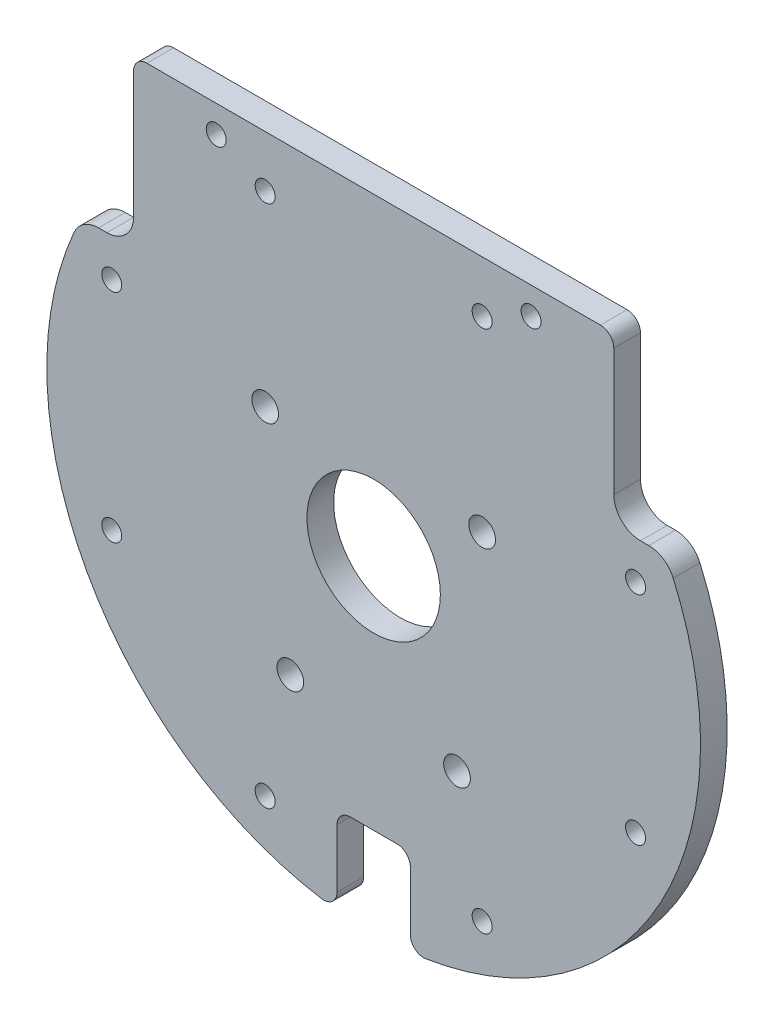
SolidWorks part; units mm, degrees
material "Hexcel AS4C (3000 丝)"
ref_plane "前视基准面" through (0, 0, 0) normal (0, 0, 1) x (1, 0, 0)
ref_plane "上视基准面" through (0, 0, 0) normal (0, 1, 0) x (1, 0, 0)
ref_plane "右视基准面" through (0, 0, 0) normal (1, 0, 0) x (0, 0, -1)
sketch "草图1" plane through (0, 0, 0) normal (0, 0, 1) x (1, 0, 0)
  line L8 (-5.5, -46.3977) -> (-5.5, -37.6103)
  line L9 (-3.5, -35.6103) -> (3.5, -35.6103)
  line L10 (5.5, -37.6103) -> (5.5, -46.3977)
  line L11 (41.2432, 22) -> (40, 22)
  line L12 (36, 26) -> (36, 45)
  line L13 (34, 47) -> (-34, 47)
  line L14 (-36, 45) -> (-36, 26)
  line L15 (-40, 22) -> (-41.2432, 22)
  line L16 (-5.5, -46.3977) -> (-5.5, -37.6103)
  line L17 (-3.5, -35.6103) -> (3.5, -35.6103)
  line L18 (5.5, -37.6103) -> (5.5, -46.3977)
  line L19 (41.2432, 22) -> (40, 22)
  line L20 (36, 26) -> (36, 45)
  line L21 (34, 47) -> (-34, 47)
  line L22 (-36, 45) -> (-36, 26)
  line L23 (-40, 22) -> (-41.2432, 22)
  circle A1 centre (0, 0) radius 10
  circle A2 centre (0, 0) radius 10
  circle A9 centre (12.5, -21.6506) radius 2
  circle A10 centre (12.5, -21.6506) radius 2
  circle A11 centre (-12.5, -21.6506) radius 2
  circle A12 centre (-12.5, -21.6506) radius 2
  circle A15 centre (-16.264, 39.2649) radius 1.5
  circle A16 centre (-16.264, 39.2649) radius 1.5
  circle A17 centre (16.264, 39.2649) radius 1.5
  circle A18 centre (16.264, 39.2649) radius 1.5
  circle A19 centre (39.2649, 16.264) radius 1.5
  circle A20 centre (39.2649, 16.264) radius 1.5
  circle A21 centre (39.2649, -16.264) radius 1.5
  circle A22 centre (39.2649, -16.264) radius 1.5
  circle A23 centre (16.264, -39.2649) radius 1.5
  circle A24 centre (16.264, -39.2649) radius 1.5
  circle A25 centre (-16.264, -39.2649) radius 1.5
  circle A26 centre (-16.264, -39.2649) radius 1.5
  circle A27 centre (-39.2649, -16.264) radius 1.5
  circle A28 centre (-39.2649, -16.264) radius 1.5
  circle A29 centre (-39.2649, 16.264) radius 1.5
  circle A30 centre (-39.2649, 16.264) radius 1.5
  arc A42 (-44.9092, 19.6) -> (-7.8191, -48.3721) centre (0, 0) ccw
  arc A43 (-7.8191, -48.3721) -> (-5.5, -46.3977) centre (-7.5, -46.3977) ccw
  arc A44 (-3.5, -35.6103) -> (-5.5, -37.6103) centre (-3.5, -37.6103) ccw
  arc A45 (5.5, -37.6103) -> (3.5, -35.6103) centre (3.5, -37.6103) ccw
  arc A46 (5.5, -46.3977) -> (7.8191, -48.3721) centre (7.5, -46.3977) ccw
  arc A47 (7.8191, -48.3721) -> (44.9092, 19.6) centre (0, 0) ccw
  arc A48 (44.9092, 19.6) -> (41.2432, 22) centre (41.2432, 18) ccw
  arc A49 (36, 26) -> (40, 22) centre (40, 26) ccw
  arc A50 (36, 45) -> (34, 47) centre (34, 45) ccw
  arc A51 (-34, 47) -> (-36, 45) centre (-34, 45) ccw
  arc A52 (-40, 22) -> (-36, 26) centre (-40, 26) ccw
  arc A53 (-41.2432, 22) -> (-44.9092, 19.6) centre (-41.2432, 18) ccw
  arc A54 (-44.9092, 19.6) -> (-7.8191, -48.3721) centre (0, 0) ccw
  arc A55 (-7.8191, -48.3721) -> (-5.5, -46.3977) centre (-7.5, -46.3977) ccw
  arc A56 (-3.5, -35.6103) -> (-5.5, -37.6103) centre (-3.5, -37.6103) ccw
  arc A57 (5.5, -37.6103) -> (3.5, -35.6103) centre (3.5, -37.6103) ccw
  arc A58 (5.5, -46.3977) -> (7.8191, -48.3721) centre (7.5, -46.3977) ccw
  arc A59 (7.8191, -48.3721) -> (44.9092, 19.6) centre (0, 0) ccw
  arc A60 (44.9092, 19.6) -> (41.2432, 22) centre (41.2432, 18) ccw
  arc A61 (36, 26) -> (40, 22) centre (40, 26) ccw
  arc A62 (36, 45) -> (34, 47) centre (34, 45) ccw
  arc A63 (-34, 47) -> (-36, 45) centre (-34, 45) ccw
  arc A64 (-40, 22) -> (-36, 26) centre (-40, 26) ccw
  arc A65 (-41.2432, 22) -> (-44.9092, 19.6) centre (-41.2432, 18) ccw
  dimension "D1" = 0
  dimension "D5" = 0
  dimension "D6" = 0
  dimension "D8" = 0
  dimension "D9" = 0
  dimension "D10" = 0
  dimension "D11" = 0
  dimension "D12" = 0
  dimension "D13" = 0
  dimension "D14" = 0
  dimension "D15" = 0
  dimension "D16" = 0
extrude "凸台-拉伸1" add sketch "草图1" along normal blind 4
sketch "草图2" plane through (0, 0, 4) normal (0, 0, 1) x (1, 0, 0)
  circle A0 centre (-16.264, 11.2649) radius 2 construction
  circle A1 centre (16.264, 11.2649) radius 2 construction
  circle A2 centre (-16.264, 11.2649) radius 2
  circle A3 centre (16.264, 11.2649) radius 2
extrude "切除-拉伸1" cut sketch "草图2" against normal through all both and the other way through all
sketch "草图3" plane through (0, 0, 0) normal (0, 0, -1) x (-1, 0, 0)
  circle A0 centre (-23.5999, 42.9444) radius 1.5 construction
  circle A1 centre (-23.5999, 42.9444) radius 1.5
extrude "切除-拉伸2" cut sketch "草图3" against normal through all both and the other way through all
sketch "草图4" plane through (0, 0, 0) normal (0, 0, -1) x (-1, 0, 0)
  circle A0 centre (23.5999, 42.9444) radius 1.5 construction
  circle A1 centre (23.5999, 42.9444) radius 1.5
extrude "切除-拉伸3" cut sketch "草图4" against normal through all both and the other way through all
